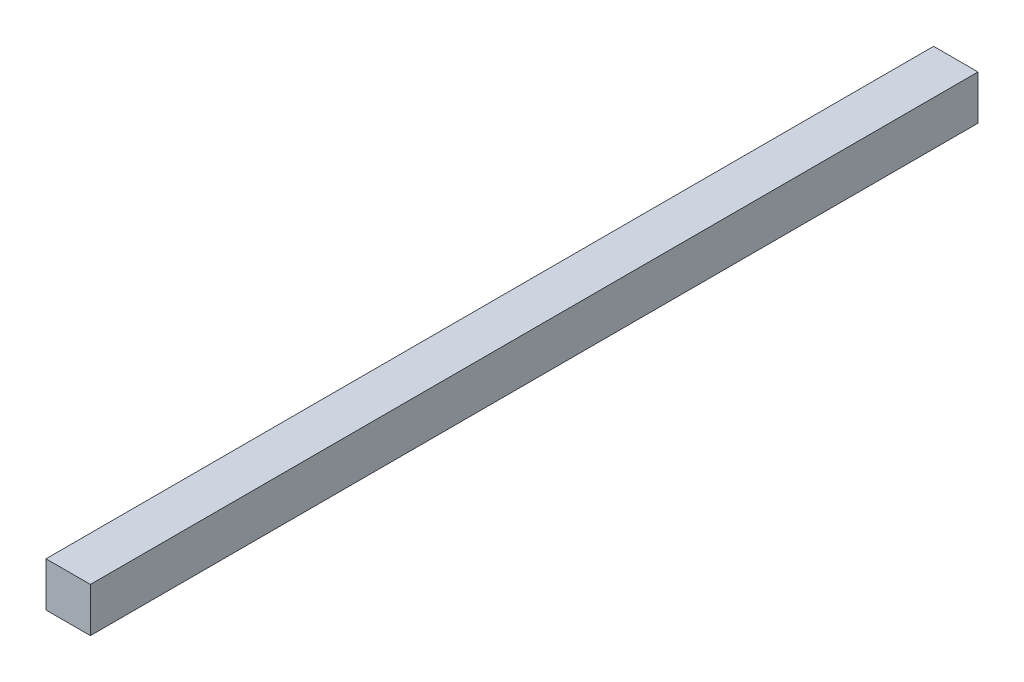
SolidWorks part; units mm, degrees
ref_plane "Front" through (0, 0, 0) normal (0, 0, 1) x (1, 0, 0)
ref_plane "Top" through (0, 0, 0) normal (0, 1, 0) x (1, 0, 0)
ref_plane "Right" through (0, 0, 0) normal (1, 0, 0) x (0, 0, -1)
other "Configuration Table"
sketch "Sketch1" plane through (0, 0, 0) normal (0, 0, 1) x (1, 0, 0)
  line L1 (0, 0) -> (25.4, 0)
  line L2 (0, 0) -> (0, 25.4)
  line L3 (0, 25.4) -> (25.4, 25.4)
  line L4 (25.4, 0) -> (25.4, 25.4)
  dimension "D1" = 25.4
extrude "Extrude1" add sketch "Sketch1" against normal blind 508
